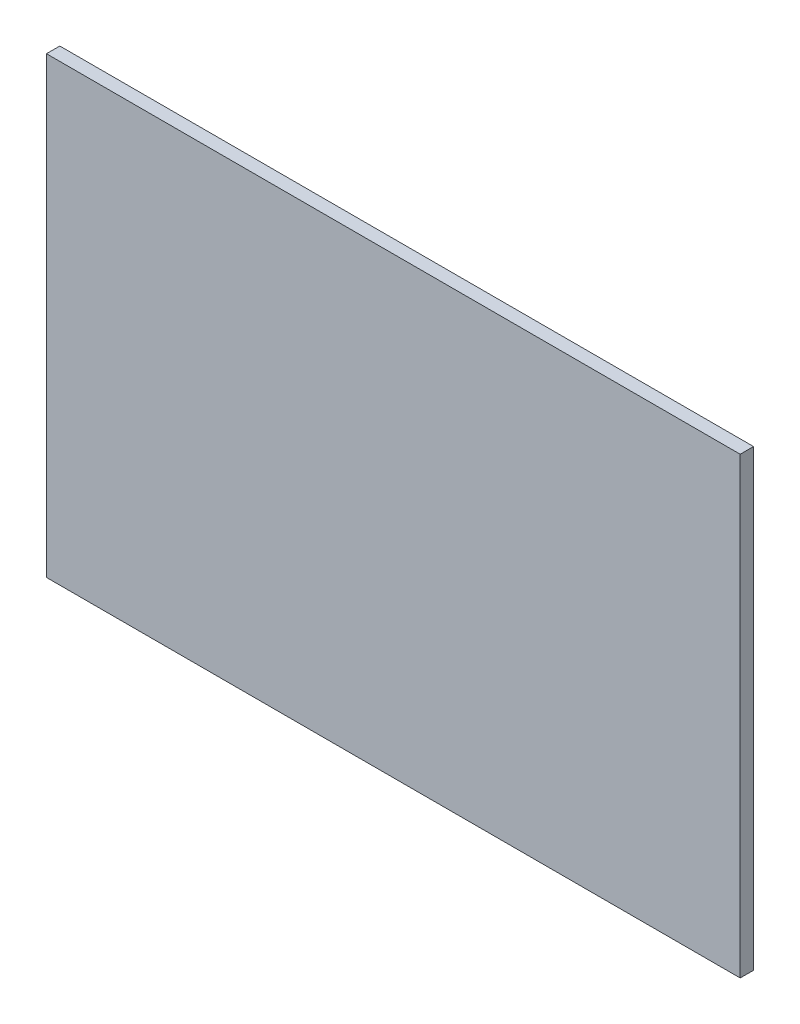
SolidWorks part; units mm, degrees
ref_plane "Front Plane" through (0, 0, 0) normal (0, 0, 1) x (1, 0, 0)
ref_plane "Top Plane" through (0, 0, 0) normal (0, 1, 0) x (1, 0, 0)
ref_plane "Right Plane" through (0, 0, 0) normal (1, 0, 0) x (0, 0, -1)
sketch "Sketch1" plane through (0, 0, 0) normal (0, 0, 1) x (1, 0, 0)
  line L1 (-99.06, 64.77) -> (99.06, 64.77)
  line L2 (-99.06, 64.77) -> (-99.06, -64.77)
  line L3 (-99.06, -64.77) -> (99.06, -64.77)
  line L4 (99.06, 64.77) -> (99.06, -64.77)
  line L5 (-99.06, 64.77) -> (99.06, -64.77) construction
  line L6 (-99.06, -64.77) -> (99.06, 64.77) construction
  point P0 (0, 0)
  dimension "D1" = 198.12
  dimension "D2" = 129.54
extrude "Boss-Extrude1" add sketch "Sketch1" along normal blind 3.81
